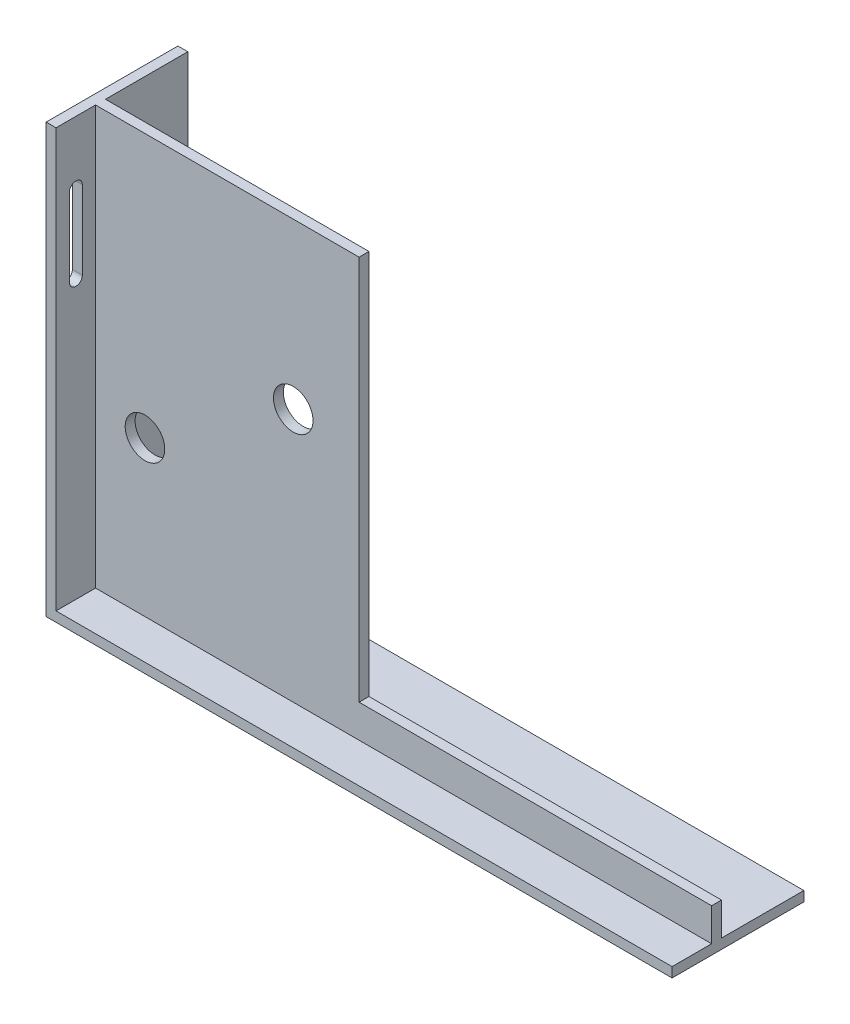
SolidWorks part; units mm, degrees
ref_plane "Front Plane" through (0, 0, 0) normal (0, 0, 1) x (1, 0, 0)
ref_plane "Top Plane" through (0, 0, 0) normal (0, 1, 0) x (1, 0, 0)
ref_plane "Right Plane" through (0, 0, 0) normal (1, 0, 0) x (0, 0, -1)
sketch "Sketch1" plane through (0, 0, 0) normal (0, 0, 1) x (1, 0, 0)
  line L1 (0, 0) -> (80, 0)
  line L2 (0, 0) -> (0, 130)
  line L3 (0, 130) -> (80, 130)
  line L4 (80, 0) -> (80, 130)
  dimension "D1" = 130
  dimension "D2" = 80
extrude "Boss-Extrude1" add sketch "Sketch1" along normal blind 3
sketch "Sketch2" plane through (0, 0, 3) normal (0, 0, 1) x (1, 0, 0)
  line L0 (0, 0) -> (80, 0) construction
  line L1 (80, 0) -> (80, 130) construction
  circle A0 centre (60, 80) radius 6
  circle A1 centre (15, 50) radius 6
  dimension "D1" = 12
  dimension "D2" = 80
  dimension "D4" = 45
  dimension "D5" = 12
  dimension "D6" = 30
  dimension "D3" = 20
extrude "Cut-Extrude1" cut sketch "Sketch2" against normal through all
sketch "Sketch3" plane through (0, 0, 0) normal (-1, 0, 0) x (0, 0, 1)
  line L0 (3, 0) -> (0, 0) construction
  line L1 (-25, 130) -> (15, 130)
  line L2 (-25, 130) -> (-25, 0)
  line L3 (-25, 0) -> (15, 0)
  line L4 (15, 130) -> (15, 0)
  line L5 (3, 130) -> (0, 130) construction
  line L6 (0, 130) -> (0, 0) construction
  dimension "D1" = 25
  dimension "D2" = 40
extrude "Boss-Extrude2" add sketch "Sketch3" along normal blind 3
sketch "Sketch4" plane through (0, 0, 0) normal (0, -1, 0) x (1, 0, 0)
  line L0 (-3, -25) -> (0, -25) construction
  line L1 (-3, 15) -> (187, 15)
  line L2 (-3, 15) -> (-3, -25)
  line L3 (-3, -25) -> (187, -25)
  line L4 (187, 15) -> (187, -25)
  dimension "D1" = 190
extrude "Boss-Extrude3" add sketch "Sketch4" against normal blind 3
sketch "Sketch5" plane through (0, 0, 0) normal (0, 0, -1) x (-1, 0, 0)
  line L0 (-80, 3) -> (-80, 130) construction
  line L1 (-80, 3) -> (-187, 3)
  line L2 (-80, 3) -> (-80, 13)
  line L3 (-80, 13) -> (-187, 13)
  line L4 (-187, 3) -> (-187, 13)
  line L5 (-80, 3) -> (0, 3) construction
  dimension "D1" = 10
extrude "Boss-Extrude4" add sketch "Sketch5" against normal up to surface (3 mm away) up to face at (66, 80, 3)
sketch "Sketch6" plane through (0, 0, 0) normal (1, 0, 0) x (0, 0, -1)
  line L0 (-8.9757, 111.0573) -> (-8.9757, 87.2648) construction
  line L1 (-7.023, 111.0573) -> (-7.023, 87.2648)
  line L2 (-10.9284, 111.0573) -> (-10.9284, 87.2648)
  arc A0 (-7.023, 111.0573) -> (-10.9284, 111.0573) centre (-8.9757, 111.0573) ccw
  arc A1 (-10.9284, 87.2648) -> (-7.023, 87.2648) centre (-8.9757, 87.2648) ccw
  point P2 (-8.9757, 99.161)
extrude "Cut-Extrude2" cut sketch "Sketch6" against normal through all
